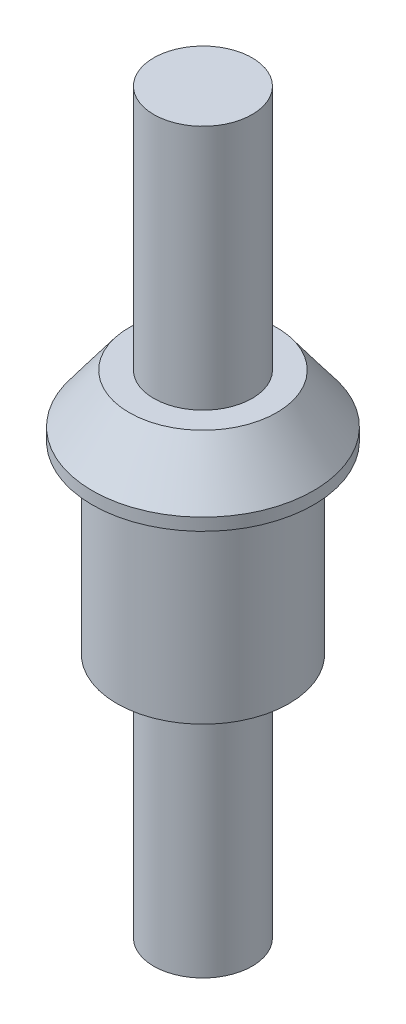
SolidWorks part; units mm, degrees
material "AISI 321 Annealed Stainless Steel (SS)"
ref_plane "Front Plane" through (0, 0, 0) normal (0, 0, 1) x (1, 0, 0)
ref_plane "Top Plane" through (0, 0, 0) normal (0, 1, 0) x (1, 0, 0)
ref_plane "Right Plane" through (0, 0, 0) normal (1, 0, 0) x (0, 0, -1)
sketch "Sketch1" plane through (0, 0, 0) normal (0, 0, 1) x (1, 0, 0)
  line L0 (0, 28.0281) -> (0, -22.5401) construction
  line L1 (0, -9.45) -> (0.4, -9.45)
  line L2 (0.4, -9.45) -> (0.4, -11.45)
  line L3 (0.4, -11.45) -> (0.6, -11.45)
  line L4 (0.9, -11.85) -> (0.9, -11.95)
  line L5 (0.9, -11.95) -> (0.7, -11.95)
  line L6 (0.7, -11.95) -> (0.7, -13.45)
  line L7 (0.7, -13.45) -> (0.4, -13.45)
  line L8 (0.4, -13.45) -> (0.4, -15.45)
  line L9 (0.4, -15.45) -> (0, -15.45)
  line L10 (0.6, -11.45) -> (0.9, -11.85)
  line L11 (0, -9.45) -> (0, -15.45)
  dimension "D1" = 1.4
  dimension "D2" = 0.8
  dimension "D3" = 1.8
  dimension "D4" = 6
  dimension "D5" = 2
  dimension "D6" = 1.5
  dimension "D7" = 2
  dimension "D8" = 0.2
  dimension "D9" = 0.1
revolve "Revolve1" add sketch "Sketch1" angle 360 about L0
